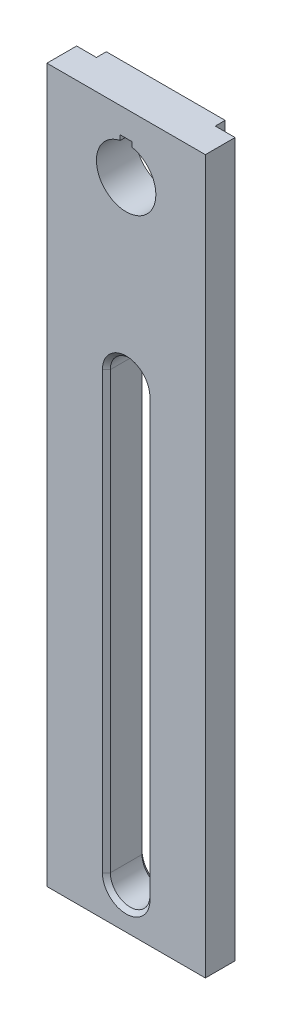
SolidWorks part; units mm, degrees
material "3.1325 (EN-AW 2017A)"
ref_plane "Płaszczyzna przednia" through (0, 0, 0) normal (0, 0, 1) x (1, 0, 0)
ref_plane "Płaszczyzna górna" through (0, 0, 0) normal (0, 1, 0) x (1, 0, 0)
ref_plane "Płaszczyzna prawa" through (0, 0, 0) normal (1, 0, 0) x (0, 0, -1)
other "Środek masy(COM)"
sketch "Szkic1" plane through (0, 0, 0) normal (0, 0, 1) x (1, 0, 0)
  line L0 (0, 20) -> (0, 200) construction
  line L1 (20, 200) -> (-20, 200)
  line L2 (-20, 200) -> (-20, 20)
  line L3 (20, 200) -> (20, 20)
  line L4 (1.4935, 193.5806) -> (-1.4935, 193.5806)
  line L5 (-1.4935, 193.5806) -> (-1.4935, 192.3498)
  line L6 (0, 140) -> (0, 30) construction
  line L7 (5, 140) -> (5, 30)
  line L8 (-5, 140) -> (-5, 30)
  line L9 (20, 20) -> (-20, 20)
  line L10 (1.4935, 193.5806) -> (1.4935, 192.3498)
  arc A0 (-1.4935, 192.3498) -> (1.4935, 192.3498) centre (0, 185) ccw
  arc A1 (5, 140) -> (-5, 140) centre (0, 140) ccw
  arc A2 (-5, 30) -> (5, 30) centre (0, 30) ccw
  point P12 (0, 85)
  point P21 (0, 193.5806)
  dimension "D1" = 40
  dimension "D2" = 15
  dimension "D5" = 60
  dimension "D7" = 7.5
  dimension "D3" = 10
  dimension "D4" = 110
  dimension "D6" = 180
  dimension "D8" = 1.4935
  dimension "D9" = 20
  dimension "D14" = 193.5806
extrude "Dodanie-wyciągnięcie1" add sketch "Szkic1" along normal blind 10
sketch "Szkic2" plane through (0, 200, 0) normal (0, 1, 0) x (1, 0, 0)
  line L0 (-20, -2.5) -> (-15, -2.5)
  line L1 (-20, -10) -> (-20, 0) construction
  line L2 (-15, -2.5) -> (-15, 0)
  line L3 (20, 0) -> (-20, 0) construction
  line L4 (0, 0) -> (0, -10) construction
  line L5 (20, -10) -> (-20, -10) construction
  line L6 (15, -2.5) -> (15, 0)
  line L7 (20, -2.5) -> (15, -2.5)
  line L8 (-20, -2.5) -> (-20, 0)
  line L9 (-20, 0) -> (-15, 0)
  line L10 (15, 0) -> (20, 0)
  line L11 (20, 0) -> (20, -2.5)
  dimension "D1" = 5
  dimension "D2" = 2.5
extrude "Wytnij-wyciągnięcie1" cut sketch "Szkic2" against normal through all
chamfer "Sfazowanie1" distance 1 angle 45 8 edges at (0, 145, 0) (-5, 85, 0) (5, 85, 0) (0, 25, 0) (0, 145, 10) (5, 85, 10) (0, 25, 10) (-5, 85, 10)
